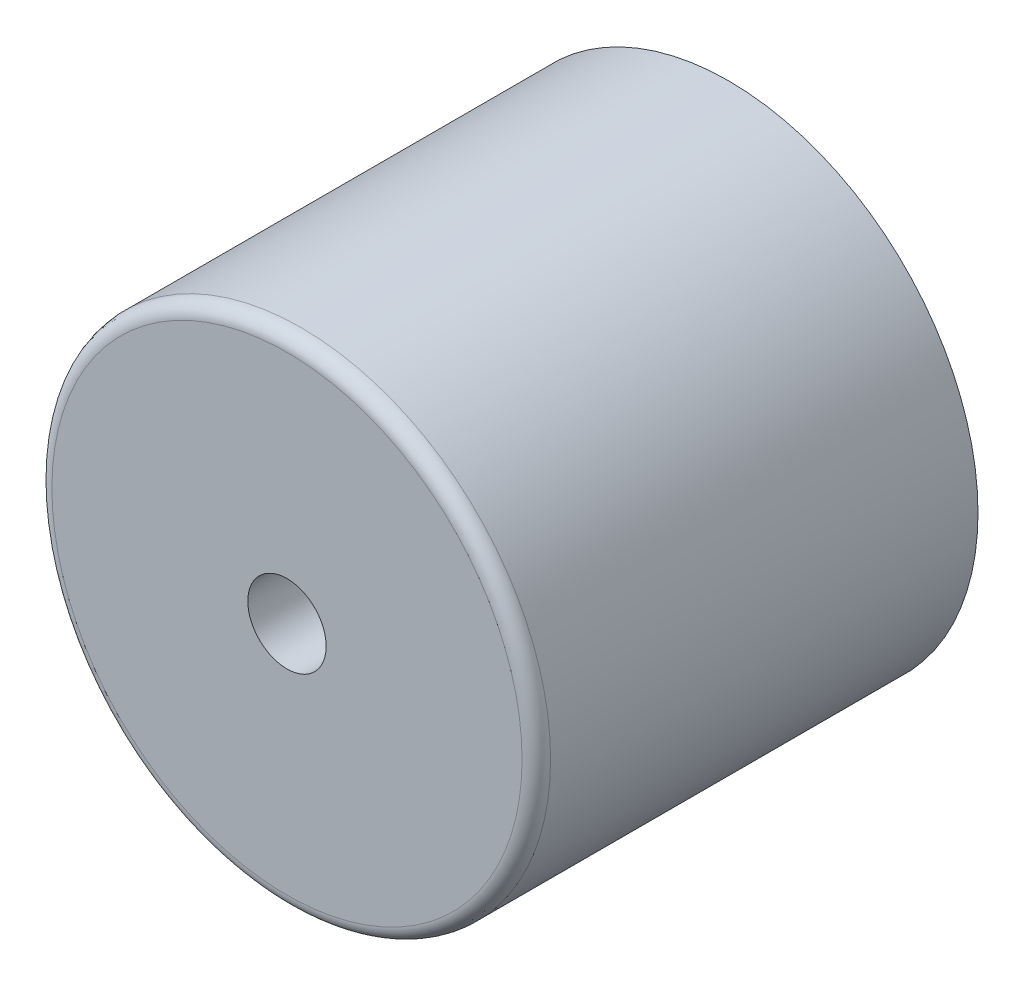
SolidWorks part; units mm, degrees
ref_plane "Piano frontale" through (0, 0, 0) normal (0, 0, 1) x (1, 0, 0)
ref_plane "Piano superiore" through (0, 0, 0) normal (0, 1, 0) x (1, 0, 0)
ref_plane "Piano destro" through (0, 0, 0) normal (1, 0, 0) x (0, 0, -1)
sketch "Schizzo1" plane through (0, 0, 0) normal (0, 0, 1) x (1, 0, 0)
  circle A0 centre (0, 0) radius 17.5
  dimension "D1" = 35
extrude "Estrusione-Estrusione1" add sketch "Schizzo1" along normal blind 31
fillet "Raccordo1" radius 1 1 edges at (17.5, 0, 31)
sketch "Schizzo2" plane through (0, 0, 0) normal (0, 0, -1) x (-1, 0, 0)
  circle A0 centre (0, 0) radius 14.25
  dimension "D1" = 28.5
extrude "Taglio-Estrusione1" cut sketch "Schizzo2" against normal blind 14
sketch "Schizzo3" plane through (0, 0, 0) normal (0, 1, 0) x (1, 0, 0)
  line L1 (16, 0) -> (14.25, 0)
  line L2 (17.5, 0) -> (16, 0) construction
  line L3 (14.25, 0) -> (-14.25, 0) construction
  line L4 (14.25, 0) -> (-14.25, 0) construction
  line L5 (14.25, 0) -> (14.25, -6)
  line L6 (16, 0) -> (14.25, -6)
  line L7 (0, 0) -> (0, -14.3058) construction
  dimension "D1" = 1.5
  dimension "D2" = 17.5
  dimension "D3" = 6
revolve "Taglia-Rivoluzione1" cut sketch "Schizzo3" angle 360 about L7
sketch "Schizzo4" plane through (0, 0, 0) normal (0, 1, 0) x (1, 0, 0)
  line L0 (14.25, -14) -> (-14.25, -14) construction
  line L1 (14.25, -14) -> (-14.25, -14) construction
  line L2 (0.25, -14) -> (0.25, -18.7)
  line L3 (0.25, -18.7) -> (9.25, -14)
  line L4 (9.25, -14) -> (0.25, -14)
  line L5 (0, -14) -> (0, -20.9981) construction
  point P4 (0, -14)
  point P6 (4.75, -14)
  dimension "D1" = 9
  dimension "D2" = 4.7
  dimension "D3" = 0.25
revolve "Taglia-Rivoluzione2" cut sketch "Schizzo4" angle 360 about L5
sketch "Schizzo5" plane through (0, 0, 14) normal (0, 0, -1) x (-1, 0, 0)
  circle A0 centre (0, 0) radius 0.25
extrude "Taglio-Estrusione2" cut sketch "Schizzo5" against normal blind 4.7
hole_wizard "Foro per Vite M5-1" positions "Schizzo3D1" profile "Schizzo6" hole size "M5" standard "ISO" end condition through all
sketch3d "Schizzo3D1"
  line L0 (0, 0, 20.0985) -> (0, 0, 49.803) construction
  point P0 (0, 0, 31)
sketch "Schizzo6" plane through (0, 0, 31) normal (1, 0, 0) x (0, -1, 0)
  line L0 (0, 0) -> (0, 31)
  line L1 (0, 31) -> (2.75, 31)
  line L2 (2.75, 31) -> (2.75, 0)
  line L5 (2.75, 0) -> (0, 0)
  line L11 (0, -6.35) -> (0, 107.95) construction
  dimension "Thru Hole Dia." = 5.5
  dimension "Thru Hole Depth" = 31
